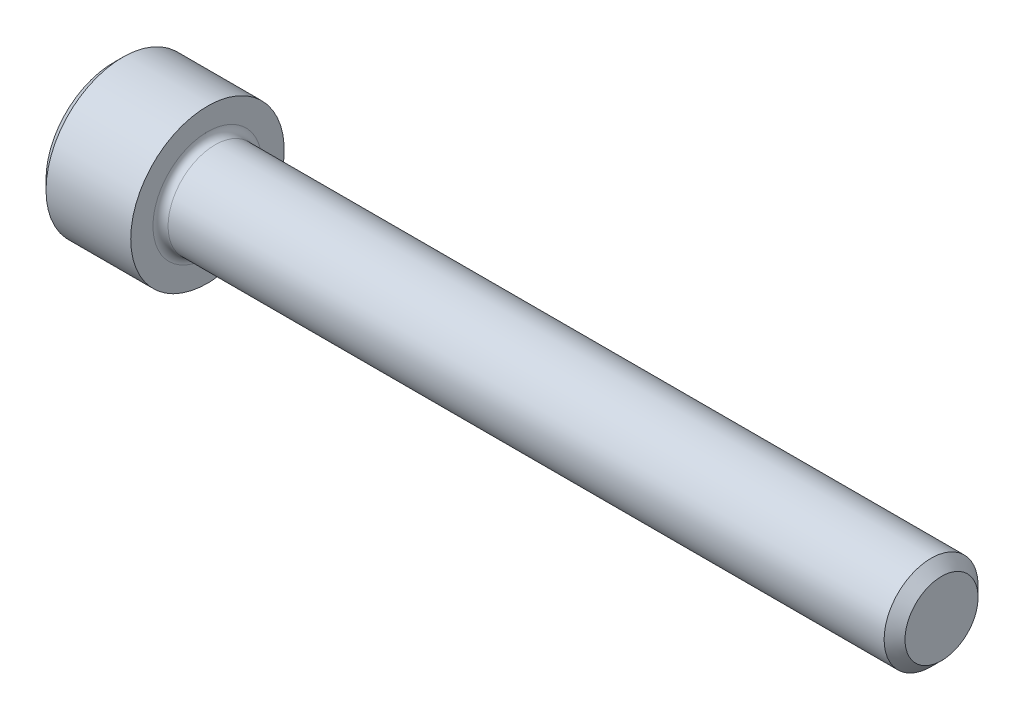
SolidWorks part; units mm, degrees
revolve "Base-Revolve" add sketch "BodySke"
sketch "BodySke" plane through (0, 0, 0) normal (0, 0, 1) x (1, 0, 0)
  line L0 (0, 0) -> (0, 2.0447)
  line L1 (0.2794, 2.3241) -> (2.8448, 2.3241)
  line L2 (2.8448, 2.3241) -> (2.8448, 1.4224)
  line L3 (2.8448, 1.4224) -> (24.7536, 1.4224)
  line L4 (25.0698, 1.1062) -> (25.0698, 0)
  line L5 (25.0698, 0) -> (0, 0)
  line L6 (-31.75, 0) -> (127, 0) construction
  line L7 (0, 2.0447) -> (0.2794, 2.3241)
  line L8 (25.0698, 1.1062) -> (24.7536, 1.4224)
  line L9 (0, -2.0447) -> (0.2794, -2.3241) construction
  line L10 (25.0698, -1.1062) -> (24.7536, -1.4224) construction
  line L11 (3.3731, 9.525) -> (3.3731, 3.175) construction
  line L12 (2.8448, 9.525) -> (2.8448, 3.175) construction
  line L13 (-13.0302, 9.525) -> (-13.0302, 3.175) construction
  dimension "Diameter" = 2.8448
  dimension "Head_ht" = 2.8448
  dimension "Length" = 22.225
  dimension "Body_ch_ang" = 45
  dimension "Head_dia" = 4.6482
  dimension "Head_ch_ang" = 45
  dimension "Head_side_ht" = 2.5654
  dimension "Minor_dia" = 2.2123
  dimension "Advance" = 0.5283
  dimension "Thread_nom" = 22.225
  dimension "Thread_length" = 38.1
cosmetic thread "ThreadCosmetic" [suppressed]
fillet "Fillet1" radius 0.2286 1 edges at (2.8448, 0, 1.4224)
material "Plastique personnalisé"
ref_plane "Plane1" through (0, 0, 0) normal (0, 0, 1) x (1, 0, 0)
ref_plane "Plane2" through (0, 0, 0) normal (0, 1, 0) x (1, 0, 0)
ref_plane "Plane3" through (0, 0, 0) normal (1, 0, 0) x (0, 0, -1)
sketch "Sketch2" plane through (0, 0, 0) normal (0, 0, 1) x (1, 0, 0)
  line L0 (0, 1.1938) -> (1.2954, 1.1938)
  line L1 (1.2954, 1.1938) -> (1.9846, 0)
  line L2 (-31.75, 0) -> (127, 0) construction
  line L3 (1.9846, 0) -> (0, 0)
  line L4 (0, 0) -> (0, 1.1938)
  line L5 (0, 2.0447) -> (0, -2.0447) construction
  line L6 (0, 0) -> (47.625, 0) construction
  line L7 (2.8448, -2.3241) -> (2.8448, 2.3241) construction
  dimension "D1" = 1.1938
  dimension "D2" = 60
revolve "Hex-PreBroach" cut sketch "Sketch2" angle 360 about L6
sketch "Sketch3" plane through (0, 0, 0) normal (-1, 0, 0) x (0, 0.5, 0.866)
  line L0 (0.6892, 1.1938) -> (-0.6892, 1.1938)
  line L1 (-0.6892, 1.1938) -> (-1.3785, 0)
  line L2 (0.6892, 1.1938) -> (1.3785, 0)
  line L3 (0.6892, -1.1938) -> (1.3785, 0)
  line L4 (0.6892, -1.1938) -> (-0.6892, -1.1938)
  line L5 (-0.6892, -1.1938) -> (-1.3785, 0)
  dimension "D1" = 1.1938
  dimension "D2" = 1.1938
  dimension "Hex_size" = 2.3876
extrude "Hex" cut sketch "Sketch3" against normal blind 1.2954
sketch "Sketch4" plane through (0, 0, 0) normal (-1, 0, 0) x (0, 0, 1)
  line L0 (0, 0) -> (1.4605, 0)
  line L1 (0, 0) -> (6.1484, 3.5498) construction
  line L2 (0, 0) -> (0.7302, 1.2648)
  line L3 (1.2009, 0.3267) -> (1.3933, 0.4378)
  line L4 (0.8834, 0.8767) -> (1.0758, 0.9877)
  arc A0 (1.2009, 0.3267) -> (0.8834, 0.8767) centre (0, 0) ccw
  arc A1 (1.4605, 0) -> (1.3933, 0.4378) centre (0, 0) ccw
  arc A2 (0.7302, 1.2648) -> (1.0758, 0.9877) centre (0, 0) cw
  dimension "D1" = 30
  dimension "D2" = 60
  dimension "Spline_p_dim" = 0.635
  dimension "D3" = 0.3175
extrude "Spline" [suppressed] cut sketch "Sketch4" against normal blind 1.2954
pattern_circular "CirPattern1" [suppressed] count 6 every 60
sketch "Sketch5" plane through (0, 0, 0) normal (0, 0, 1) x (1, 0, 0)
  line L0 (-31.75, 0) -> (127, 0) construction
  line L2 (0, 2.0447) -> (0, -2.0447) construction
  circle A0 centre (1.016, 0) radius 0.4445
  dimension "Drilled_hole_dia" = 0.889
  dimension "Drilled_hole_loc" = 1.016
extrude "Hole" [suppressed] cut sketch "Sketch5" against normal through all and the other way through all
pattern_circular "Drilled-4" [suppressed] count 2 every 60
pattern_circular "Drilled-6" [suppressed] count 3 every 60
sketch "ThdSchSke" plane through (0, 0, 0) normal (0, 0, 1) x (1, 0, 0)
  line L0 (3.3731, -1.1062) -> (3.1517, -1.4224)
  line L1 (3.3731, -1.1062) -> (3.5945, -1.4224)
  line L2 (3.5945, -1.4224) -> (3.5945, -1.778)
  line L3 (-3.175, 0) -> (5.1513, 0) construction
  line L5 (3.5945, -1.778) -> (3.1517, -1.778)
  line L6 (3.1517, -1.778) -> (3.1517, -1.4224)
  line L7 (0, 2.0447) -> (0, -2.0447) construction
  dimension "Thread_minor" = 2.2123
  dimension "Diameter" = 2.8448
  dimension "Start" = 3.3731
revolve "ThreadSchematic" [suppressed] cut sketch "ThdSchSke" angle 360 about L3
pattern_linear "ThdSchPat" [suppressed]
equation "\"D2@Sketch3\" = \"Hex_size@Sketch3\" / 2"
equation "\"D1@Sketch3\" = \"Hex_size@Sketch3\" / 2"
equation "\"D1@Sketch2\" = \"Hex_size@Sketch3\" / 2"
equation "\"D3@Sketch4\" = \"Spline_p_dim@Sketch4\" / 2"
equation "\"Thread_minor@ThreadCosmetic\"  =  \"Minor_dia@BodySke\""
equation "\"D2@CirPattern1\" = 360 / \"Num_teeth@CirPattern1\""
equation "\"Wall_thickness@Sketch2\" = \"Head_ht@BodySke\" - \"Key_eng@Hex\""
equation "\"Thread_length@ThreadCosmetic\" = ((sgn( (\"Length@BodySke\" - \"Advance@BodySke\" ) - \"Thread_nom@BodySke\" )-1)*( (\"Length@BodySke\" - \"Advance@BodySke\" ) - \"Thread_nom@BodySke\" ))/-2+ \"Thread_nom@BodySke\""
equation "\"Thread_minor@ThdSchSke\" = \"Minor_dia@BodySke\""
equation "\"Diameter@ThdSchSke\" = \"Diameter@BodySke\""
equation "\"Overcut@ThdSchSke\" = \"Diameter@BodySke\" * 1.25"
equation "\"Start@ThdSchSke\" = \"Head_ht@BodySke\" + \"Length@BodySke\" - \"Thread_length@ThreadCosmetic\"  '---Non-countersunk---"
equation "\"Num_threads@ThdSchPat\" = int( \"Thread_length@ThreadCosmetic\" / \"Advance@BodySke\" + 0.999 )  + 1"
equation "\"Advance@ThdSchPat\" = \"Thread_length@ThreadCosmetic\" /  (\"Num_threads@ThdSchPat\" - 1) 'relax it"
equation "\"Num_threads@ThdSchPat\" = \"Num_threads@ThdSchPat\" - sgn( \"Num_threads@ThdSchPat\" - 1) '---chamfered tips only---"
